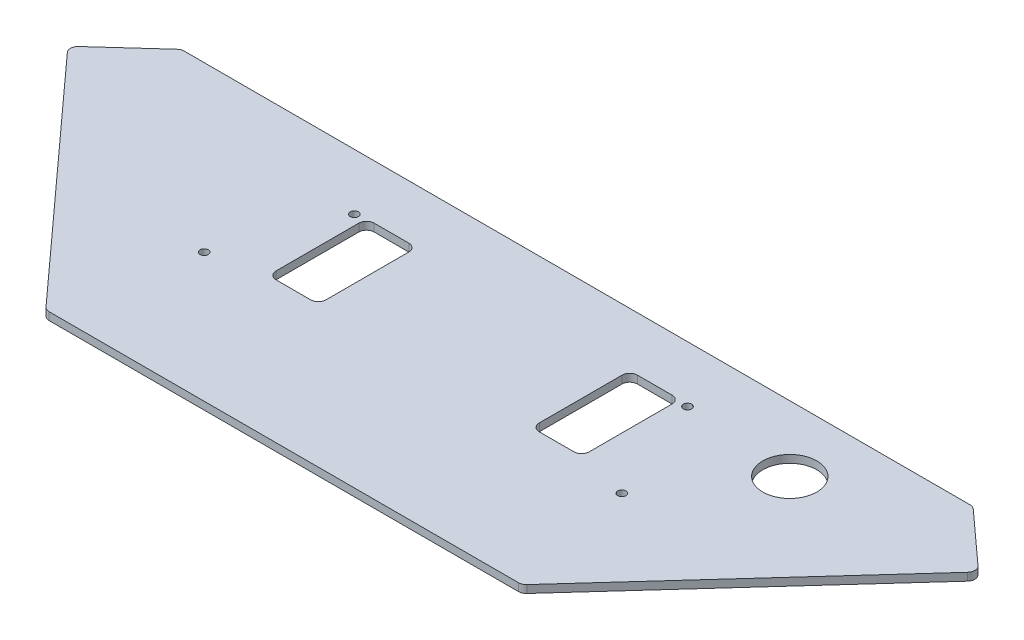
SolidWorks part; units mm, degrees
ref_plane "Front Plane" through (0, 0, 0) normal (0, 0, 1) x (1, 0, 0)
ref_plane "Top Plane" through (0, 0, 0) normal (0, 1, 0) x (1, 0, 0)
ref_plane "Right Plane" through (0, 0, 0) normal (1, 0, 0) x (0, 0, -1)
sketch "Sketch1" plane through (0, 0, 0) normal (0, 1, 0) x (1, 0, 0)
  line L0 (-97.9674, 0) -> (97.9674, 0)
  line L1 (97.9674, 0) -> (187.3367, 98.457)
  line L2 (162.887, 120.65) -> (-162.887, 120.65)
  line L3 (-187.3367, 98.457) -> (-97.9674, 0)
  line L4 (0, 0) -> (0, 33.02) construction
  line L5 (-187.3367, 98.457) -> (-162.887, 120.65)
  line L6 (187.3367, 98.457) -> (162.887, 120.65)
  point P5 (0, 120.65)
  dimension "D1" = 120.65
  dimension "D2" = 84.46
  dimension "D3" = 325.7739
  dimension "D4" = 33.02
extrude "Boss-Extrude1" add sketch "Sketch1" along normal blind 3.175
sketch "Sketch2" plane through (0, 3.175, 0) normal (0, 1, 0) x (1, 0, 0)
  line L0 (0, 0) -> (0, 50000) construction
  line L1 (-61.2648, 58.039) -> (-47.0408, 58.039)
  line L2 (-64.4398, 61.214) -> (-64.4398, 95.25)
  line L3 (-61.2648, 98.425) -> (-47.0408, 98.425)
  line L4 (-43.8658, 61.214) -> (-43.8658, 95.25)
  line L5 (-64.4398, 58.039) -> (-43.8658, 98.425) construction
  line L6 (-64.4398, 98.425) -> (-43.8658, 58.039) construction
  line L7 (43.8658, 61.214) -> (43.8658, 95.25)
  line L8 (61.2648, 98.425) -> (47.0408, 98.425)
  line L9 (64.4398, 61.214) -> (64.4398, 95.25)
  line L10 (61.2648, 58.039) -> (47.0408, 58.039)
  line L11 (162.887, 120.65) -> (-162.887, 120.65) construction
  line L13 (-97.9674, 0) -> (97.9674, 0) construction
  arc A0 (43.8658, 95.25) -> (47.0408, 98.425) centre (47.0408, 95.25) cw
  arc A1 (61.2648, 98.425) -> (64.4398, 95.25) centre (61.2648, 95.25) cw
  arc A2 (64.4398, 61.214) -> (61.2648, 58.039) centre (61.2648, 61.214) cw
  arc A3 (43.8658, 61.214) -> (47.0408, 58.039) centre (47.0408, 61.214) ccw
  arc A4 (-61.2648, 58.039) -> (-64.4398, 61.214) centre (-61.2648, 61.214) cw
  arc A5 (-47.0408, 58.039) -> (-43.8658, 61.214) centre (-47.0408, 61.214) ccw
  arc A6 (-47.0408, 98.425) -> (-43.8658, 95.25) centre (-47.0408, 95.25) cw
  arc A7 (-64.4398, 95.25) -> (-61.2648, 98.425) centre (-61.2648, 95.25) cw
  point P0 (-54.1528, 78.232)
  point P8 (54.1528, 78.232)
  point P19 (43.8658, 98.425)
  point P22 (64.4398, 98.425)
  point P25 (64.4398, 58.039)
  point P28 (43.8658, 58.039)
  dimension "D6" = 3.175
  dimension "D1" = 20.574
  dimension "D2" = 40.386
  dimension "D3" = 108.3056
  dimension "D4" = 22.225
  dimension "D5" = 58.039
extrude "Cut-Extrude1" cut sketch "Sketch2" against normal through all
sketch "Sketch3" plane through (0, 3.175, 0) normal (0, 1, 0) x (1, 0, 0)
  line L0 (61.2648, 98.425) -> (47.0408, 98.425) construction
  line L1 (0, 117.6274) -> (0, 61.993) construction
  line L2 (64.4398, 61.214) -> (64.4398, 95.25) construction
  line L3 (162.887, 120.65) -> (-162.887, 120.65) construction
  circle A0 centre (68.5292, 97.536) radius 1.7018
  circle A1 centre (85.9282, 53.1114) radius 1.7018
  circle A2 centre (-85.9282, 53.1114) radius 1.7018
  circle A3 centre (-68.5292, 97.536) radius 1.7018
  point P13 (68.5292, 97.536)
  point P18 (0, 120.65)
  point P23 (85.9282, 53.1114)
  dimension "D3" = 3.4036
  dimension "D6" = 3.4036
  dimension "D1" = 21.4884
  dimension "D2" = 0.889
  dimension "D4" = 44.4246
extrude "Cut-Extrude2" cut sketch "Sketch3" against normal up to surface (3.175 mm away) up to face at (54.1528, 0, -78.232)
fillet "Fillet1" radius 3.175 6 edges at (-187.3367, 1.5875, -98.457) (-162.887, 1.5875, -120.65) (162.887, 1.5875, -120.65) (187.3367, 1.5875, -98.457) (97.9674, 1.5875, 0) (-97.9674, 1.5875, 0)
sketch "Sketch4" plane through (0, 3.175, 0) normal (0, 1, 0) x (1, 0, 0)
  line L0 (61.2648, 98.425) -> (47.0408, 98.425) construction
  line L1 (161.6609, 120.65) -> (-161.6609, 120.65) construction
  circle A0 centre (114.4778, 93.6625) radius 11.1125
  point P4 (54.1528, 98.425)
  dimension "D3" = 22.225
  dimension "D1" = 60.325
  dimension "D2" = 26.9875
extrude "Cut-Extrude3" cut sketch "Sketch4" against normal through all
